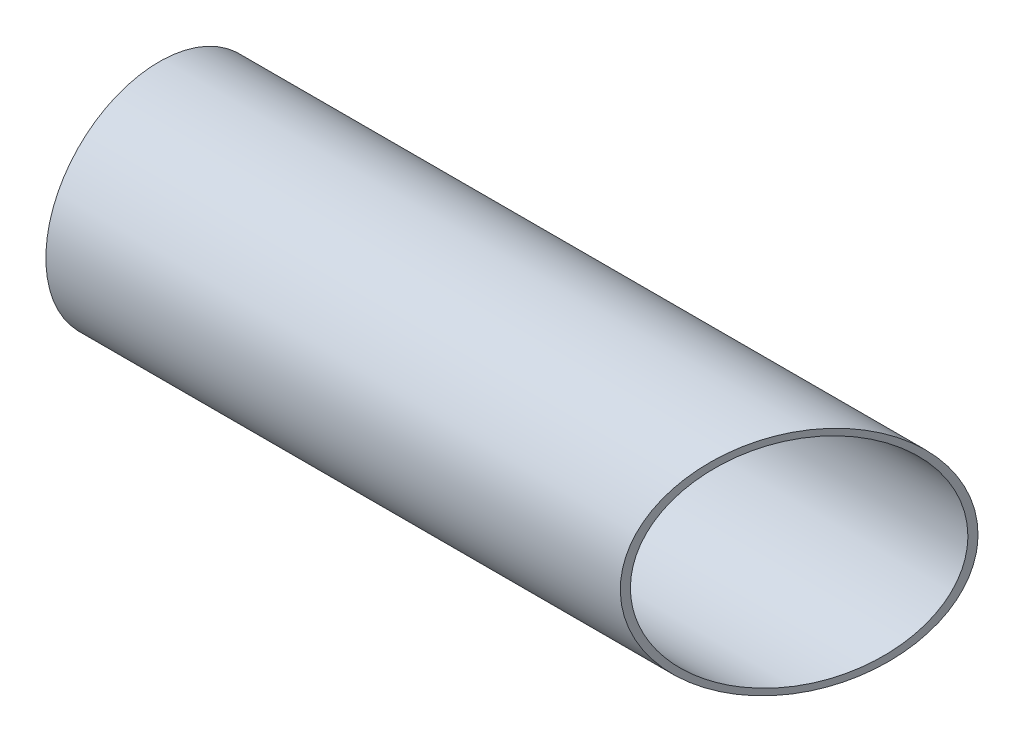
SolidWorks part; units mm, degrees
ref_plane "Front Plane" through (0, 0, 0) normal (0, 0, 1) x (1, 0, 0)
ref_plane "Top Plane" through (0, 0, 0) normal (0, 1, 0) x (1, 0, 0)
ref_plane "Right Plane" through (0, 0, 0) normal (1, 0, 0) x (0, 0, -1)
sketch "Sketch2" plane through (0, 0, 0) normal (0, 1, 0) x (1, 0, 0)
  line L1 (-404.1452, -700) -> (404.1452, -700)
  line L2 (404.1452, -700) -> (808.2904, 0)
  line L3 (808.2904, 0) -> (404.1452, 700)
  line L4 (404.1452, 700) -> (-404.1452, 700)
  line L5 (-404.1452, 700) -> (-808.2904, 0)
  line L6 (-808.2904, 0) -> (-404.1452, -700)
  circle A0 centre (0, 0) radius 700 construction
  dimension "D1" = 700
sketch "Sketch3" plane through (0, 0, 0) normal (1, 0, 0) x (0, 0, -1)
  circle A0 centre (-700, 0) radius 50
  circle A1 centre (-700, 0) radius 53
  dimension "D1" = 100
  dimension "D2" = 3
sweep "Sweep1" add profiles "Sketch3" path "Sketch2"
sketch "Sketch4" plane through (0, 0, 0) normal (0, 1, 0) x (1, 0, 0)
  line L0 (-235, -407.0319) -> (-487.5, -844.3748) construction
  line L1 (0, -975) -> (0, 0) construction
  line L2 (-235, -407.0319) -> (-235, -946.2558) construction
  line L3 (-235, -407.0319) -> (0, 0) construction
  line L4 (0, 0) -> (487.5, 844.3748) construction
  line L5 (105.0452, 181.9436) -> (105.0452, 969.3248) construction
  line L6 (487.5, 844.3748) -> (105.0452, 181.9436)
  line L7 (105.0452, 181.9436) -> (105.0452, 969.3248)
  circle A0 centre (0, 0) radius 975 construction
  dimension "D1" = 1950
  dimension "D2" = 235
  dimension "D3" = 299.1
split "Split1" trim tools "Sketch4" bodies to split 101 resulting bodies 103
